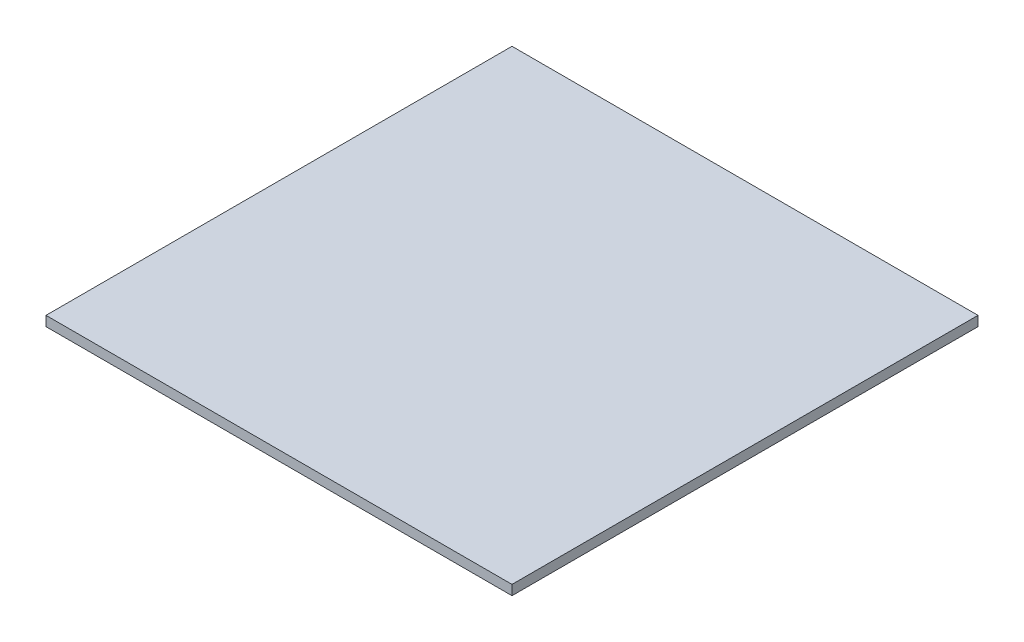
SolidWorks part; units mm, degrees
ref_plane "Front Plane" through (0, 0, 0) normal (0, 0, 1) x (1, 0, 0)
ref_plane "Top Plane" through (0, 0, 0) normal (0, 1, 0) x (1, 0, 0)
ref_plane "Right Plane" through (0, 0, 0) normal (1, 0, 0) x (0, 0, -1)
sketch "Sketch1" plane through (0, 0, 0) normal (0, 0, 1) x (1, 0, 0)
  line L1 (0, 0) -> (950, 0)
  line L2 (0, 0) -> (0, 20)
  line L3 (0, 20) -> (950, 20)
  line L4 (950, 0) -> (950, 20)
  dimension "D1" = 950
  dimension "D2" = 20
extrude "Reference_only" add sketch "Sketch1" along normal blind 950
